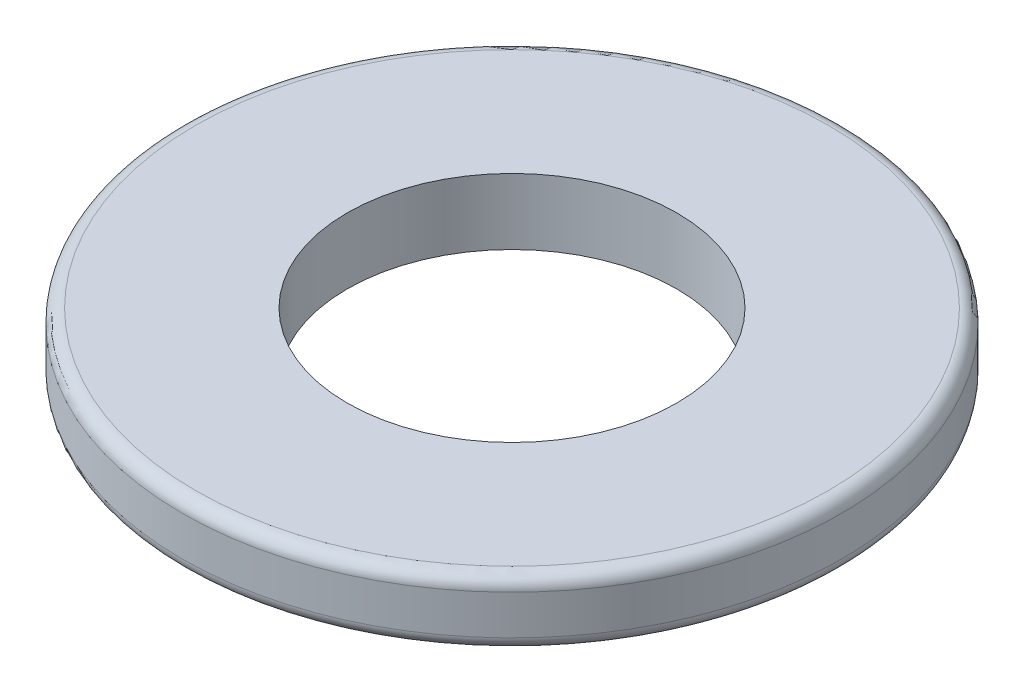
SolidWorks part; units mm, degrees
ref_plane "Front Plane" through (0, 0, 0) normal (0, 0, 1) x (1, 0, 0)
ref_plane "Top Plane" through (0, 0, 0) normal (0, 1, 0) x (1, 0, 0)
ref_plane "Right Plane" through (0, 0, 0) normal (1, 0, 0) x (0, 0, -1)
sketch "Sketch1" plane through (0, 0, 0) normal (0, 1, 0) x (1, 0, 0)
  circle A0 centre (0, 0) radius 1.25
  circle A1 centre (0, 0) radius 2.5
  dimension "D1" = 2.5
  dimension "D2" = 5
extrude "Boss-Extrude1" add sketch "Sketch1" along normal blind 0.5
fillet "Fillet1" radius 0.1 2 edges at (0, 0, 2.5) (0, 0.5, 2.5)
